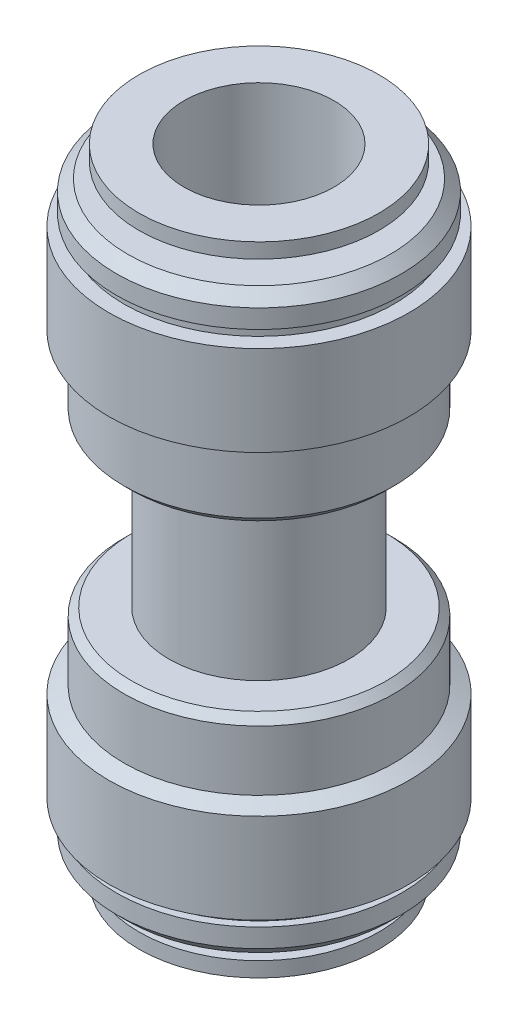
SolidWorks part; units mm, degrees
ref_plane "Спереди" through (0, 0, 0) normal (0, 0, 1) x (1, 0, 0)
ref_plane "Сверху" through (0, 0, 0) normal (0, 1, 0) x (1, 0, 0)
ref_plane "Справа" through (0, 0, 0) normal (1, 0, 0) x (0, 0, -1)
sketch "Эскиз1" plane through (0, 0, 0) normal (0, 0, 1) x (1, 0, 0)
  line L1 (0, 136.374) -> (0, -118.2669) construction
  line L2 (8, 1) -> (6, 1)
  line L3 (0, 0) -> (8, 0)
  line L4 (8, 0) -> (8, 1)
  line L6 (6, 2) -> (8.75, 2)
  line L7 (9.5, 2.75) -> (9.5, 4)
  line L8 (8.75, 2) -> (9.5, 2.75)
  line L9 (9.5, 4) -> (9, 4)
  line L10 (9, 4) -> (9, 4.75)
  line L11 (9, 4.75) -> (10, 4.75)
  line L12 (10, 4.75) -> (10, 10.75)
  line L13 (9, 15.25) -> (8.5, 15.75)
  line L14 (9, 11.25) -> (9, 15.25)
  line L15 (8.5, 15.75) -> (6, 15.75)
  line L16 (6, 15.75) -> (6, 26.75)
  line L17 (0, 42.5) -> (0, 0)
  line L18 (9, 11.25) -> (10, 10.75)
  line L20 (9, 31.25) -> (10, 31.75)
  line L21 (8.5, 26.75) -> (6, 26.75)
  line L22 (9, 31.25) -> (9, 27.25)
  line L23 (9, 27.25) -> (8.5, 26.75)
  line L24 (10, 37.75) -> (10, 31.75)
  line L25 (9, 37.75) -> (10, 37.75)
  line L26 (9, 38.5) -> (9, 37.75)
  line L27 (9.5, 38.5) -> (9, 38.5)
  line L28 (8.75, 40.5) -> (9.5, 39.75)
  line L29 (9.5, 39.75) -> (9.5, 38.5)
  line L30 (6, 40.5) -> (8.75, 40.5)
  line L32 (8, 42.5) -> (8, 41.5)
  line L33 (0, 42.5) -> (8, 42.5)
  line L34 (8, 41.5) -> (6, 41.5)
  line L36 (6, 1) -> (6, 2)
  line L37 (6, 41.5) -> (6, 40.5)
  point P10 (9.5, 2)
  point P19 (9, 15.75)
  point P27 (4, 21.25)
  point P30 (6, 21.25)
  point P43 (9, 26.75)
  point P44 (9.5, 40.5)
revolve "Повернуть1" add sketch "Эскиз1" angle 360 about L1
sketch "Эскиз2" plane through (0, 42.5, 0) normal (0, 1, 0) x (1, 0, 0)
  circle A0 centre (0, 0) radius 5
  dimension "D1" = 10
extrude "Вырез-Вытянуть1" cut sketch "Эскиз2" against normal blind 60
